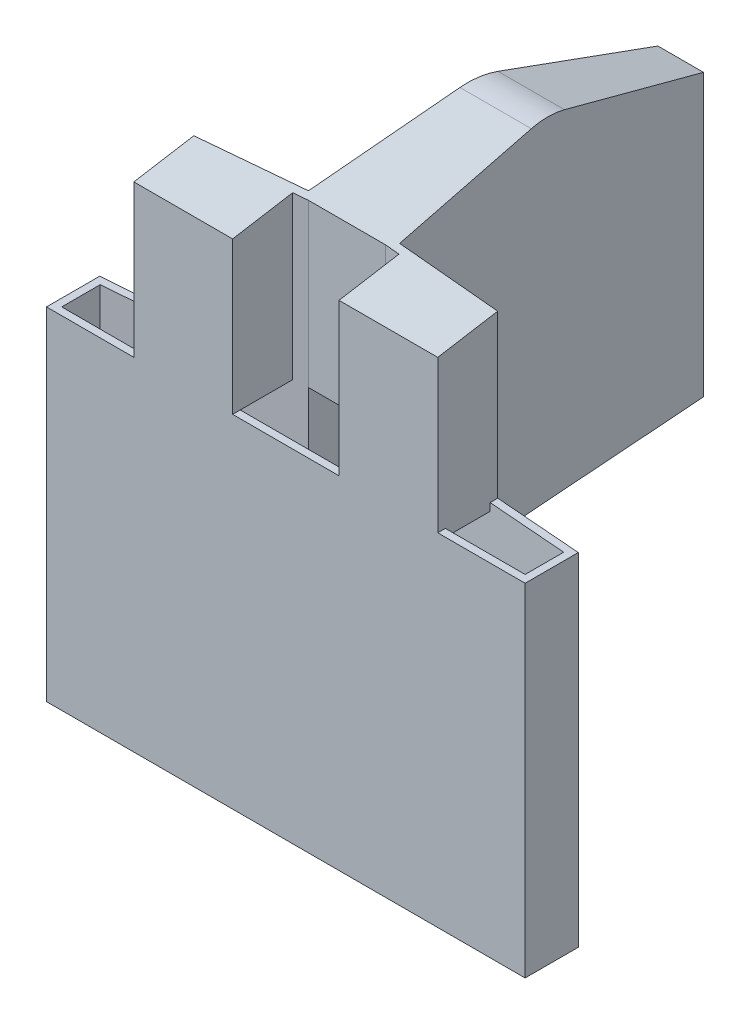
SolidWorks part; units mm, degrees
ref_plane "Front Plane" through (0, 0, 0) normal (0, 0, 1) x (1, 0, 0)
ref_plane "Top Plane" through (0, 0, 0) normal (0, 1, 0) x (1, 0, 0)
ref_plane "Right Plane" through (0, 0, 0) normal (1, 0, 0) x (0, 0, -1)
sketch "Sketch2" plane through (0, 0, 0) normal (0, 1, 0) x (1, 0, 0)
  line L0 (-18.9886, 28.3829) -> (-4.9886, 29.4702)
  line L1 (-30.4886, 20.4898) -> (32.5114, 20.4898)
  line L2 (-30.4886, 20.4898) -> (-30.4886, 27.4898)
  line L5 (-1.9886, 72.4702) -> (4.0114, 72.4702)
  line L10 (-1.9886, 72.4702) -> (-4.9886, 29.4702)
  line L17 (4.0114, 72.4702) -> (7.0114, 29.4702)
  line L22 (32.5114, 20.4898) -> (32.5114, 27.4898)
  line L23 (-30.4886, 27.4898) -> (-18.9886, 28.3829)
  line L25 (7.0114, 29.4702) -> (32.5114, 27.4898)
  dimension "D4" = 43
  dimension "D5" = 25.5
extrude "Boss-Extrude1" add sketch "Sketch2" along normal blind 70 contours L0 L10 L5 L17 L25 L22 L1 L2 L23
sketch "Sketch3" plane through (0, 70, 0) normal (0, 1, 0) x (1, 0, 0)
  line L1 (-30.4886, 27.4898) -> (-30.4886, 20.4898)
  line L2 (-30.4886, 20.4898) -> (-18.9886, 20.4898)
  line L3 (-30.4886, 20.4898) -> (32.5114, 20.4898) construction
  line L6 (21.0114, 20.4898) -> (32.5114, 20.4898)
  line L7 (32.5114, 20.4898) -> (32.5114, 27.4898)
  line L9 (-18.9886, 20.4898) -> (-18.9886, 28.3829)
  line L10 (-30.4886, 27.4898) -> (-4.9886, 29.4702) construction
  line L12 (21.0114, 20.4898) -> (21.0114, 28.3829)
  line L23 (-18.9886, 28.3829) -> (-30.4886, 27.4898)
  line L24 (21.0114, 28.3829) -> (32.5114, 27.4898)
  dimension "D1" = 40
extrude "Cut-Extrude1" cut sketch "Sketch3" against normal blind 25 contours L1 L2 L9 L23 | L6 L7 L24 L12
sketch "Sketch7" plane through (0, 0, 0) normal (1, 0, 0) x (0, 0, -1)
  line L0 (20.4898, 70) -> (20.4898, 65)
  line L1 (20.4898, 45) -> (20.4898, 70) construction
  line L2 (20.4898, 65) -> (50.4898, 70)
  line L3 (72.4702, 70) -> (29.4702, 70) construction
  line L4 (50.4898, 70) -> (20.4898, 70)
  line L5 (50.4898, 70) -> (72.4702, 70)
  line L6 (72.4702, 70) -> (72.4702, 63)
  line L7 (72.4702, 63) -> (50.4898, 70)
  dimension "D1" = 30
  dimension "D2" = 5
  dimension "D3" = 7
extrude "Cut-Extrude4" cut sketch "Sketch7" against normal blind 27 and the other way blind 24 contours L2 L4 L0 | L7 L6 L5
shell "Shell2" thickness 1
fillet "Fillet1" radius 10 1 edges at (1.0114, 70, -50.4898)
sketch "Sketch6" plane through (0, 0, 0) normal (0, -1, 0) x (1, 0, 0)
  line L0 (-4.9886, -29.4702) -> (7.0114, -29.4702)
  line L1 (7.0114, -29.4702) -> (4.0114, -72.4702)
  line L2 (4.0114, -72.4702) -> (-1.9886, -72.4702)
  line L3 (-1.9886, -72.4702) -> (-4.9886, -29.4702)
extrude "Cut-Extrude3" cut sketch "Sketch6" against normal blind 26
sketch "Sketch4" plane through (0, 45, 0) normal (0, 1, 0) x (1, 0, 0)
  line L0 (1.0114, 72.4702) -> (1.0114, 20.4898) construction
  line L7 (-18.9886, 28.3829) -> (-30.4886, 27.4898) construction
  line L8 (31.5114, 21.4898) -> (21.0114, 21.4898)
  line L9 (21.0114, 27.3799) -> (21.0114, 21.4898)
  line L19 (31.5114, 26.5644) -> (21.0114, 27.3799)
  line L23 (31.5114, 21.4898) -> (31.5114, 26.5644)
  line L36 (-29.4886, 21.4898) -> (-29.4886, 26.5644)
  line L37 (-29.4886, 26.5644) -> (-18.9886, 27.3799)
  line L38 (-18.9886, 20.4898) -> (-18.9886, 28.3829) construction
  line L39 (-18.9886, 27.3799) -> (-18.9886, 21.4898)
  line L42 (-29.4886, 21.4898) -> (-18.9886, 21.4898)
  line L43 (-30.4886, 20.4898) -> (-18.9886, 20.4898) construction
  line L44 (-30.4886, 27.4898) -> (-30.4886, 20.4898) construction
  dimension "D1" = 1
  dimension "D2" = 1
  dimension "D3" = 1
extrude "Cut-Extrude2" cut sketch "Sketch4" against normal blind 1
ref_plane "Plane1" through (0, 45, 0) normal (0, -1, 0) x (-1, 0, 0)
sketch "Sketch16" plane through (0, 45, 0) normal (0, -1, 0) x (-1, 0, 0)
  line L0 (-6.009, 29.4702) -> (3.9861, 29.4702)
  line L1 (3.9861, 29.4702) -> (4.051, 28.54)
  line L2 (4.051, 28.54) -> (-6.0739, 28.54)
  line L3 (-6.0739, 28.54) -> (-6.009, 29.4702)
extrude "Boss-Extrude4" add sketch "Sketch16" against normal blind 21.5
sketch "Sketch19" plane through (0, 45, 0) normal (0, -1, 0) x (-1, 0, 0)
  line L0 (5.9886, 28.3896) -> (5.9886, 21.4898)
  line L1 (17.9886, 27.4576) -> (4.051, 28.54) construction
  line L2 (5.9886, 28.3896) -> (6.9886, 28.3119)
  line L3 (29.4886, 26.5644) -> (4.051, 28.54) construction
  line L4 (6.9886, 28.3119) -> (6.9886, 21.4898)
  line L5 (29.4886, 21.4898) -> (-31.5114, 21.4898) construction
  line L6 (6.9886, 21.4898) -> (5.9886, 21.4898)
  line L7 (-8.0114, 21.4898) -> (-8.0114, 28.3896)
  line L8 (-6.0739, 28.54) -> (-31.5114, 26.5644) construction
  line L9 (-8.0114, 28.3896) -> (-9.0114, 28.3119)
  line L10 (-9.0114, 28.3119) -> (-9.0114, 21.4898)
  line L11 (-20.0114, 21.4898) -> (17.9886, 21.4898) construction
  line L12 (-9.0114, 21.4898) -> (-8.0114, 21.4898)
  dimension "D1" = 1
  dimension "D2" = 1
extrude "Boss-Extrude5" add sketch "Sketch19" against normal blind 22
sketch "Sketch20" plane through (-5.9886, 0, 0) normal (1, 0, 0) x (0, 0, -1)
  line L0 (21.4898, 67) -> (21.4898, 65.1667)
  line L1 (28.3829, 66.3155) -> (20.4898, 65) construction
  line L2 (21.4898, 65.1667) -> (28.3119, 66.3037) construction
  line L9 (21.4898, 67) -> (30.6098, 67)
  line L10 (30.6098, 67) -> (30.6098, 66.6867)
  line L11 (48.1101, 69.6034) -> (29.4702, 66.4967) construction
  line L12 (30.6098, 66.6867) -> (21.4898, 65.1667)
extrude "Cut-Extrude8" cut sketch "Sketch20" against normal mid plane 40
sketch "Sketch22" plane through (0, 45, 0) normal (0, -1, 0) x (-1, 0, 0)
  line L0 (-8.0114, 28.3896) -> (-8.0114, 20.4898)
  line L1 (30.4886, 20.4898) -> (-32.5114, 20.4898) construction
  line L2 (5.9886, 28.3896) -> (5.9886, 20.4898)
  line L3 (5.9886, 20.4898) -> (-8.0114, 20.4898)
  line L4 (-8.0114, 28.3896) -> (-6.0739, 28.54)
  line L5 (-6.0739, 28.54) -> (4.051, 28.54)
  line L6 (4.051, 28.54) -> (5.9886, 28.3896)
extrude "Cut-Extrude10" cut sketch "Sketch22" against normal blind 34
